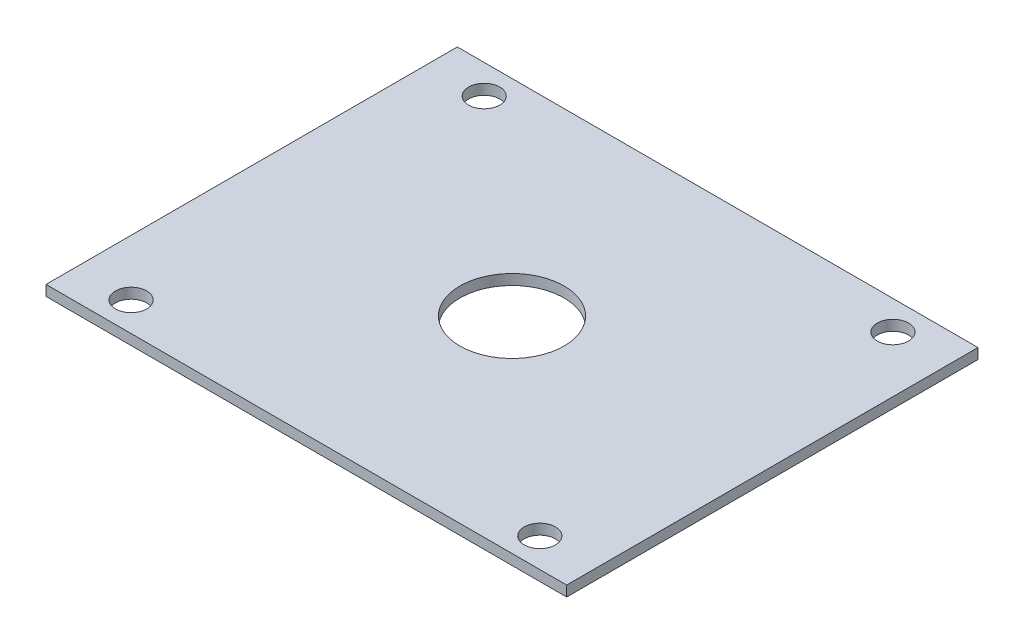
SolidWorks part; units mm, degrees
material "Thornel VCB-20 Carbon Cloth"
ref_plane "Front Plane" through (0, 0, 0) normal (0, 0, 1) x (1, 0, 0)
ref_plane "Top Plane" through (0, 0, 0) normal (0, 1, 0) x (1, 0, 0)
ref_plane "Right Plane" through (0, 0, 0) normal (1, 0, 0) x (0, 0, -1)
sketch "Sketch1" plane through (0, 0, 0) normal (0, 1, 0) x (1, 0, 0)
  line L1 (-25, -19.75) -> (25, -19.75)
  line L2 (-25, -19.75) -> (-25, 19.75)
  line L3 (-25, 19.75) -> (25, 19.75)
  line L4 (25, -19.75) -> (25, 19.75)
  circle A0 centre (-19.625, 16.955) radius 1.5
  circle A1 centre (-19.625, -16.955) radius 1.5
  circle A2 centre (19.625, 16.955) radius 1.5
  circle A3 centre (19.625, -16.955) radius 1.5
  point P0 (0, 0)
  point P6 (0, 0)
  dimension "D5" = 3
  dimension "D6" = 3
  dimension "D7" = 3
  dimension "D8" = 3
  dimension "D1" = 50
  dimension "D2" = 39.5
  dimension "D3" = 39.25
  dimension "D4" = 33.91
extrude "Boss-Extrude1" add sketch "Sketch1" along normal blind 1
sketch "Sketch2" plane through (0, 1, 0) normal (0, 1, 0) x (1, 0, 0)
  circle A0 centre (0, 0) radius 5
  dimension "D1" = 10
extrude "Cut-Extrude1" cut sketch "Sketch2" against normal blind 1
